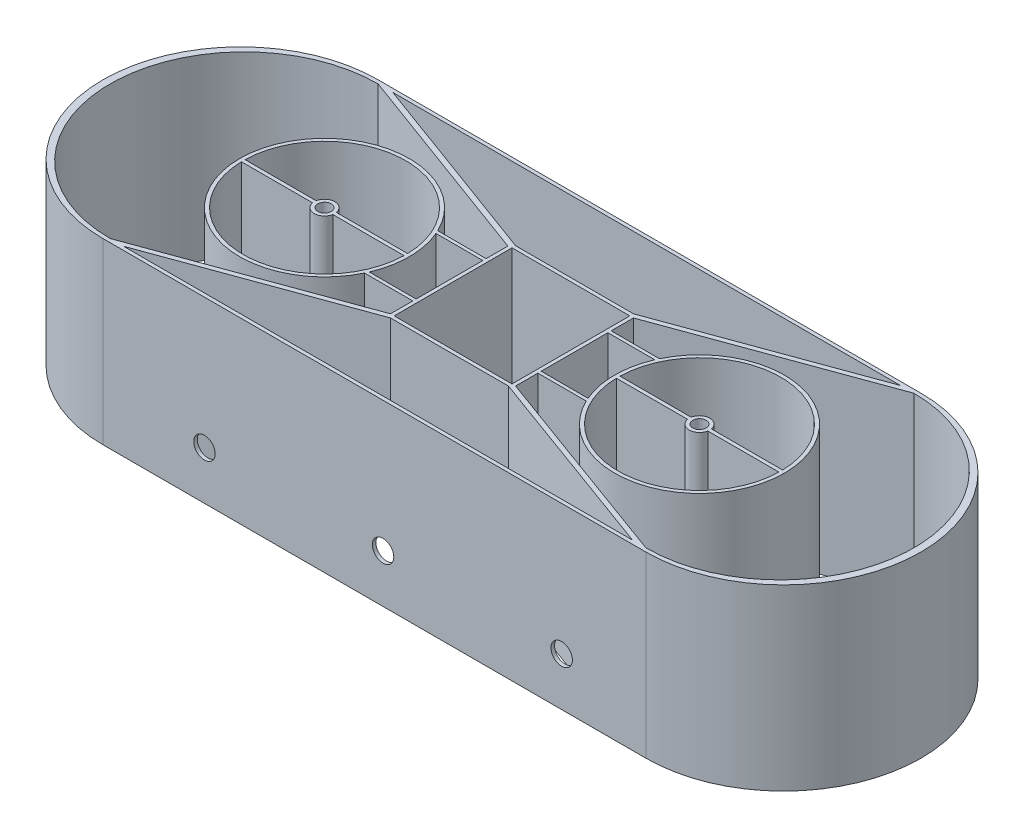
SolidWorks part; units mm, degrees
ref_plane "Front Plane" through (0, 0, 0) normal (0, 0, 1) x (1, 0, 0)
ref_plane "Top Plane" through (0, 0, 0) normal (0, 1, 0) x (1, 0, 0)
ref_plane "Right Plane" through (0, 0, 0) normal (1, 0, 0) x (0, 0, -1)
sketch "Sketch1" plane through (0, 0, 0) normal (0, 1, 0) x (1, 0, 0)
  line L0 (33, 0) -> (35, 0) construction
  line L3 (-141.6976, 75) -> (142.5238, 75)
  line L6 (-142.5238, -75) -> (142.5238, -75)
  line L8 (-152, 77) -> (152, 77)
  line L9 (-152, -77) -> (152, -77)
  line L10 (-35, 32.6808) -> (-150, 75)
  line L11 (-33, 35) -> (33, 35)
  line L12 (-35, 32.6808) -> (-35, 20.5012)
  line L13 (-33, -35) -> (33, -35)
  line L14 (35, 33) -> (35, 20.5012)
  line L17 (-33, 33) -> (33, 33)
  line L18 (-33, 33) -> (-33, -33)
  line L19 (-33, -33) -> (33, -33)
  line L20 (33, 33) -> (33, -33)
  line L23 (-33, 35) -> (-141.6976, 75)
  line L24 (-35, -33) -> (-150, -75)
  line L25 (-33, -35) -> (-142.5238, -75)
  line L26 (35, -33) -> (150, -75)
  line L27 (33, -35) -> (142.5238, -75)
  line L28 (35, 33) -> (150, 75)
  line L29 (33, 35) -> (142.5238, 75)
  line L30 (-62.0702, 20.5012) -> (-35, 20.5012)
  line L31 (-61.2493, 18.687) -> (-35, 18.687)
  line L32 (-35, 18.687) -> (-35, -18.687)
  line L33 (-62.0702, -20.5012) -> (-35, -20.5012)
  line L34 (-61.2493, -18.687) -> (-35, -18.687)
  line L35 (-35, -20.5012) -> (-35, -33)
  line L36 (0, -55) -> (0, 55) construction
  line L37 (62.0702, -20.5012) -> (35, -20.5012)
  line L38 (61.2493, -18.687) -> (35, -18.687)
  line L39 (61.2493, 18.687) -> (35, 18.687)
  line L40 (62.0702, 20.5012) -> (35, 20.5012)
  line L41 (35, 18.687) -> (35, -18.687)
  line L42 (35, -20.5012) -> (35, -33)
  line L43 (-150.4961, 1) -> (-110.6303, 1)
  line L44 (-150.4961, -1) -> (-110.6303, -1)
  line L46 (-59.4338, -1) -> (-99.2996, -1)
  line L47 (-59.4338, 1) -> (-99.2996, 1)
  line L48 (59.4338, 1) -> (99.2996, 1)
  line L49 (59.4338, -1) -> (99.2996, -1)
  line L50 (150.4961, -1) -> (110.6303, -1)
  line L51 (150.4961, 1) -> (110.6303, 1)
  line L52 (-35, 0) -> (-33, 0) construction
  arc A4 (-150, 75) -> (-150, -75) centre (-150, 0) ccw
  arc A5 (150, -75) -> (150, 75) centre (150, 0) ccw
  arc A6 (-152, 77) -> (-152, -77) centre (-152, 0) ccw
  arc A7 (152, -77) -> (152, 77) centre (152, 0) ccw
  arc A8 (-62.0702, 20.5012) -> (-62.0702, -20.5012) centre (-104.965, 0) ccw
  arc A9 (-150.4961, -1) -> (-59.4338, -1) centre (-104.965, 0) ccw
  arc A10 (-61.2493, -18.687) -> (-61.2493, 18.687) centre (-104.965, 0) ccw
  arc A11 (61.2493, -18.687) -> (61.2493, 18.687) centre (104.965, 0) cw
  arc A12 (62.0702, 20.5012) -> (62.0702, -20.5012) centre (104.965, 0) cw
  arc A13 (59.4338, 1) -> (150.4961, 1) centre (104.965, 0) cw
  circle A14 centre (-104.965, 0) radius 3.75
  arc A15 (-110.6303, -1) -> (-99.2996, -1) centre (-104.965, 0) ccw
  arc A16 (-99.2996, 1) -> (-110.6303, 1) centre (-104.965, 0) ccw
  arc A17 (-59.4338, 1) -> (-150.4961, 1) centre (-104.965, 0) ccw
  circle A18 centre (104.965, 0) radius 3.75
  arc A19 (110.6303, -1) -> (99.2996, -1) centre (104.965, 0) cw
  arc A20 (99.2996, 1) -> (110.6303, 1) centre (104.965, 0) cw
  arc A21 (150.4961, -1) -> (59.4338, -1) centre (104.965, 0) cw
  point P2 (0, 0)
  point P3 (0, 0)
  point P8 (-75, 0)
  point P9 (75, 0)
  point P12 (0, 0)
  point P22 (0, 0)
  dimension "D2" = 150
  dimension "D3" = 2
  dimension "D4" = 2
  dimension "D6" = 2
  dimension "D7" = 2
  dimension "D8" = 11.5058
  dimension "D1" = 150
  dimension "D5" = 2
  dimension "D9" = 2
extrude "Boss-Extrude1" add sketch "Sketch1" along normal blind 100
ref_plane "Plane1" through (0, 0, 77) normal (0, 0, 1) x (1, 0, 0)
sketch "Sketch2" plane through (0, 0, 77) normal (0, 0, 1) x (1, 0, 0)
  line L0 (-152, 0) -> (152, 0) construction
  circle A0 centre (4.8138, 27.007) radius 6
  circle A1 centre (104.8138, 27.007) radius 6
  circle A2 centre (-95.1862, 27.007) radius 6
  dimension "D1" = 12
  dimension "D5" = 12
  dimension "D3" = 100
  dimension "D4" = 100
  dimension "D6" = 27.007
  dimension "D2" = 2
extrude "Cut-Extrude1" cut sketch "Sketch2" against normal blind 10
ref_plane "Plane2" through (0, 0, -77) normal (0, 0, -1) x (-1, 0, 0)
sketch "Sketch4" plane through (0, 0, -77) normal (0, 0, -1) x (-1, 0, 0)
  line L0 (-152, 0) -> (152, 0) construction
  circle A0 centre (0, 27.1) radius 10.2787
  circle A1 centre (100, 27.1) radius 10.2787
  circle A2 centre (-100, 27.1) radius 10.2787
  dimension "D1" = 27.1
  dimension "D2" = 100
  dimension "D3" = 100
extrude "Cut-Extrude2" cut sketch "Sketch4" against normal blind 10
